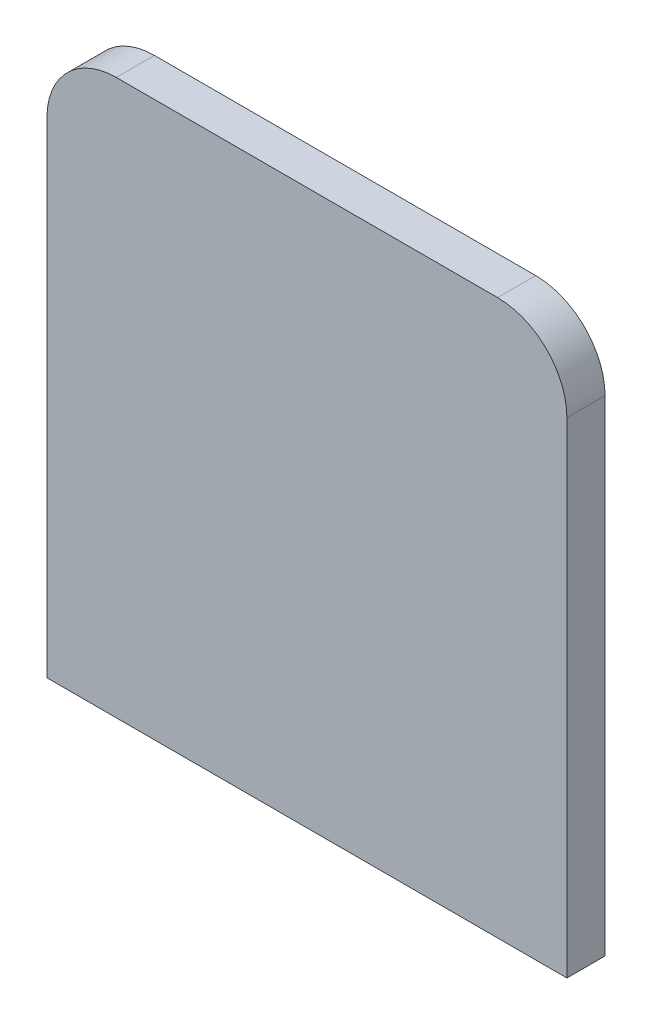
SolidWorks part; units mm, degrees
ref_plane "前视基准面" through (0, 0, 0) normal (0, 0, 1) x (1, 0, 0)
ref_plane "上视基准面" through (0, 0, 0) normal (0, 1, 0) x (1, 0, 0)
ref_plane "右视基准面" through (0, 0, 0) normal (1, 0, 0) x (0, 0, -1)
sketch "草图1" plane through (0, 0, 0) normal (0, 0, 1) x (1, 0, 0)
  line L0 (0, 16) -> (5.5, 16)
  line L1 (7.5, 14) -> (7.5, 0)
  line L2 (0, 16) -> (-5.5, 16)
  line L3 (-7.5, 14) -> (-7.5, 0)
  line L4 (0, 0) -> (7.5, 0)
  line L5 (0, 0) -> (-7.5, 0)
  arc A0 (7.5, 14) -> (5.5, 16) centre (5.5, 14) ccw
  arc A1 (-5.5, 16) -> (-7.5, 14) centre (-5.5, 14) ccw
  point P2 (-54.8389, 0)
  dimension "D1" = 0
  dimension "D2" = 0
extrude "凸台-拉伸1" add sketch "草图1" along normal blind 1.1 contours L3 L5 L4 L1 A0 L0 L2 A1
